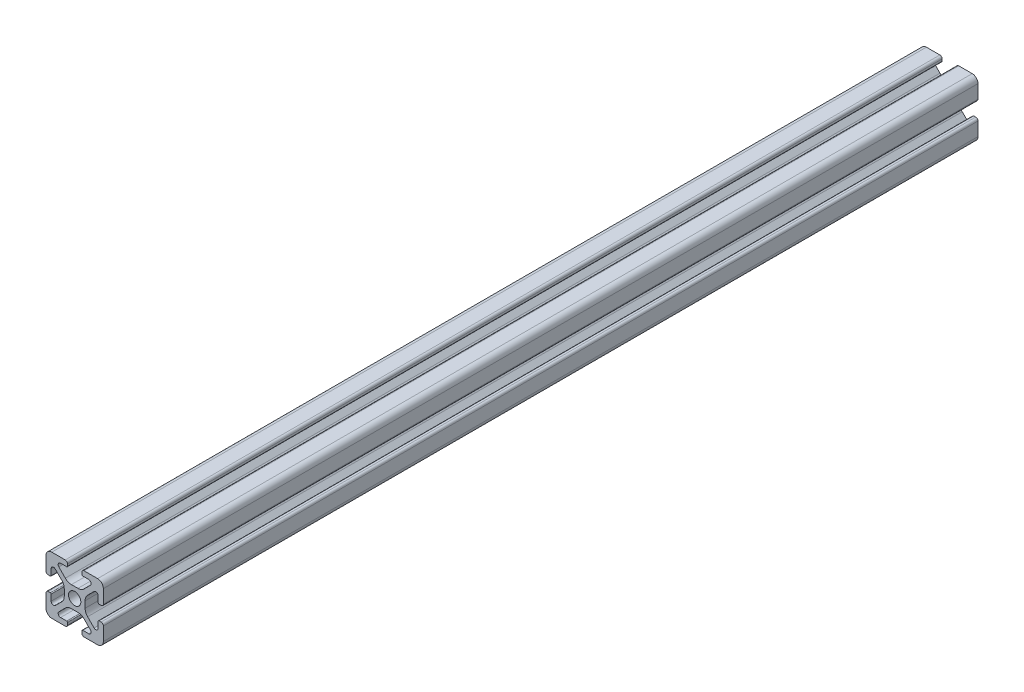
SolidWorks part; units mm, degrees
ref_plane "Front Plane" through (0, 0, 0) normal (0, 0, 1) x (1, 0, 0)
ref_plane "Top Plane" through (0, 0, 0) normal (0, 1, 0) x (1, 0, 0)
ref_plane "Right Plane" through (0, 0, 0) normal (1, 0, 0) x (0, 0, -1)
sketch "Sketch1" plane through (0, 0, 0) normal (0, 0, 1) x (1, 0, 0)
  line L2 (-9.9949, 7.9883) -> (-9.9949, 3.2893)
  line L3 (-7.9883, 9.9949) -> (-3.2893, 9.9949)
  line L4 (-2.5019, 9.2075) -> (-2.5019, 8.4963)
  line L5 (-2.8067, 8.1915) -> (-4.9149, 8.1915)
  line L6 (-5.5076, 6.7606) -> (-3.2528, 4.5058)
  line L7 (-6.7606, 5.5076) -> (-4.5058, 3.2528)
  line L8 (-8.1915, 4.9149) -> (-8.1915, 2.8067)
  line L9 (-8.4963, 2.5019) -> (-9.2075, 2.5019)
  line L11 (-1.1334, 3.6279) -> (1.1334, 3.6279)
  line L12 (-3.6279, 1.1334) -> (-3.6279, -1.1334)
  line L13 (8.4963, 2.5019) -> (9.2075, 2.5019)
  line L14 (8.1915, 4.9149) -> (8.1915, 2.8067)
  line L15 (9.9949, 7.9883) -> (9.9949, 3.2893)
  line L16 (7.9883, 9.9949) -> (3.2893, 9.9949)
  line L17 (2.5019, 9.2075) -> (2.5019, 8.4963)
  line L18 (2.8067, 8.1915) -> (4.9149, 8.1915)
  line L19 (3.6279, 1.1334) -> (3.6279, -1.1334)
  line L20 (5.5076, 6.7606) -> (3.2528, 4.5058)
  line L21 (6.7606, 5.5076) -> (4.5058, 3.2528)
  line L22 (-8.4963, -2.5019) -> (-9.2075, -2.5019)
  line L23 (-8.1915, -4.9149) -> (-8.1915, -2.8067)
  line L24 (-6.7606, -5.5076) -> (-4.5058, -3.2528)
  line L25 (-5.5076, -6.7606) -> (-3.2528, -4.5058)
  line L26 (-2.8067, -8.1915) -> (-4.9149, -8.1915)
  line L27 (-2.5019, -9.2075) -> (-2.5019, -8.4963)
  line L28 (-7.9883, -9.9949) -> (-3.2893, -9.9949)
  line L29 (-9.9949, -7.9883) -> (-9.9949, -3.2893)
  line L30 (9.9949, -7.9883) -> (9.9949, -3.2893)
  line L31 (7.9883, -9.9949) -> (3.2893, -9.9949)
  line L32 (2.5019, -9.2075) -> (2.5019, -8.4963)
  line L33 (2.8067, -8.1915) -> (4.9149, -8.1915)
  line L34 (5.5076, -6.7606) -> (3.2528, -4.5058)
  line L35 (6.7606, -5.5076) -> (4.5058, -3.2528)
  line L36 (8.1915, -4.9149) -> (8.1915, -2.8067)
  line L37 (8.4963, -2.5019) -> (9.2075, -2.5019)
  line L38 (-1.1334, -3.6279) -> (1.1334, -3.6279)
  circle A0 centre (0, 0) radius 2.1463
  arc A1 (-9.9949, 7.9883) -> (-7.9883, 9.9949) centre (-7.9883, 7.9883) cw
  arc A2 (-6.7606, 5.5076) -> (-8.1915, 4.9149) centre (-7.3533, 4.9149) ccw
  arc A3 (-4.9149, 8.1915) -> (-5.5076, 6.7606) centre (-4.9149, 7.3533) ccw
  arc A4 (-3.2893, 9.9949) -> (-2.5019, 9.2075) centre (-3.2893, 9.2075) cw
  arc A5 (-9.9949, 3.2893) -> (-9.2075, 2.5019) centre (-9.2075, 3.2893) ccw
  arc A6 (-8.1915, 2.8067) -> (-8.4963, 2.5019) centre (-8.4963, 2.8067) cw
  arc A7 (-2.5019, 8.4963) -> (-2.8067, 8.1915) centre (-2.8067, 8.4963) cw
  arc A8 (-1.1334, 3.6279) -> (-3.2528, 4.5058) centre (-1.1334, 6.6251) cw
  arc A9 (-3.6279, 1.1334) -> (-4.5058, 3.2528) centre (-6.6251, 1.1334) ccw
  arc A10 (8.1915, 2.8067) -> (8.4963, 2.5019) centre (8.4963, 2.8067) ccw
  arc A11 (9.9949, 3.2893) -> (9.2075, 2.5019) centre (9.2075, 3.2893) cw
  arc A12 (9.9949, 7.9883) -> (7.9883, 9.9949) centre (7.9883, 7.9883) ccw
  arc A13 (3.2893, 9.9949) -> (2.5019, 9.2075) centre (3.2893, 9.2075) ccw
  arc A14 (2.5019, 8.4963) -> (2.8067, 8.1915) centre (2.8067, 8.4963) ccw
  arc A15 (1.1334, 3.6279) -> (3.2528, 4.5058) centre (1.1334, 6.6251) ccw
  arc A16 (3.6279, 1.1334) -> (4.5058, 3.2528) centre (6.6251, 1.1334) cw
  arc A17 (6.7606, 5.5076) -> (8.1915, 4.9149) centre (7.3533, 4.9149) cw
  arc A18 (4.9149, 8.1915) -> (5.5076, 6.7606) centre (4.9149, 7.3533) cw
  arc A19 (-3.6279, -1.1334) -> (-4.5058, -3.2528) centre (-6.6251, -1.1334) cw
  arc A20 (-1.1334, -3.6279) -> (-3.2528, -4.5058) centre (-1.1334, -6.6251) ccw
  arc A21 (-2.5019, -8.4963) -> (-2.8067, -8.1915) centre (-2.8067, -8.4963) ccw
  arc A22 (-8.1915, -2.8067) -> (-8.4963, -2.5019) centre (-8.4963, -2.8067) ccw
  arc A23 (-9.9949, -3.2893) -> (-9.2075, -2.5019) centre (-9.2075, -3.2893) cw
  arc A24 (-3.2893, -9.9949) -> (-2.5019, -9.2075) centre (-3.2893, -9.2075) ccw
  arc A25 (-4.9149, -8.1915) -> (-5.5076, -6.7606) centre (-4.9149, -7.3533) cw
  arc A26 (-6.7606, -5.5076) -> (-8.1915, -4.9149) centre (-7.3533, -4.9149) cw
  arc A27 (-9.9949, -7.9883) -> (-7.9883, -9.9949) centre (-7.9883, -7.9883) ccw
  arc A28 (9.9949, -7.9883) -> (7.9883, -9.9949) centre (7.9883, -7.9883) cw
  arc A29 (6.7606, -5.5076) -> (8.1915, -4.9149) centre (7.3533, -4.9149) ccw
  arc A30 (4.9149, -8.1915) -> (5.5076, -6.7606) centre (4.9149, -7.3533) ccw
  arc A31 (3.2893, -9.9949) -> (2.5019, -9.2075) centre (3.2893, -9.2075) cw
  arc A32 (9.9949, -3.2893) -> (9.2075, -2.5019) centre (9.2075, -3.2893) ccw
  arc A33 (8.1915, -2.8067) -> (8.4963, -2.5019) centre (8.4963, -2.8067) cw
  arc A34 (2.5019, -8.4963) -> (2.8067, -8.1915) centre (2.8067, -8.4963) cw
  arc A35 (1.1334, -3.6279) -> (3.2528, -4.5058) centre (1.1334, -6.6251) cw
  arc A36 (3.6279, -1.1334) -> (4.5058, -3.2528) centre (6.6251, -1.1334) ccw
  dimension "D4" = 0.8382
  dimension "D5" = 2.9972
  dimension "D6" = 0.3048
  dimension "D1" = 9.8298
  dimension "D2" = 4.5636
  dimension "D3" = 3.7254
  dimension "D7" = 5.0038
  dimension "D8" = 1.8034
extrude "Boss-Extrude1" add sketch "Sketch1" along normal mid plane 304.8
